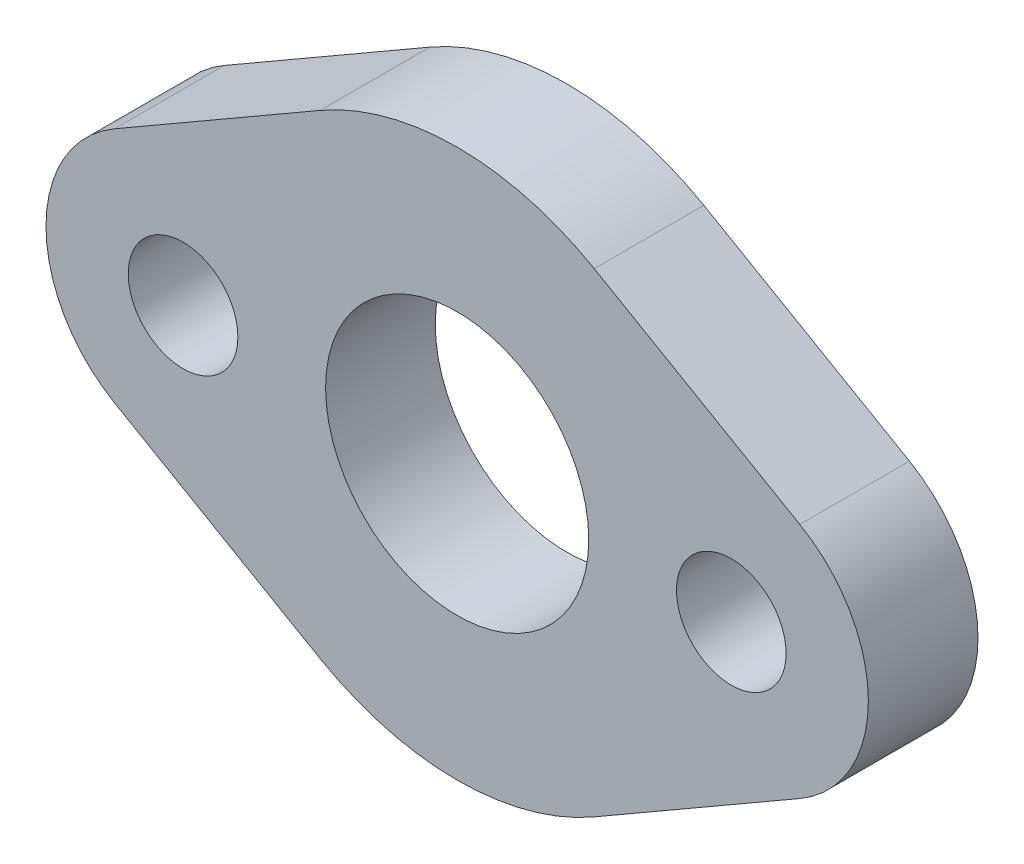
SolidWorks part; units mm, degrees
ref_plane "前视基准面" through (0, 0, 0) normal (0, 0, 1) x (1, 0, 0)
ref_plane "上视基准面" through (0, 0, 0) normal (0, 1, 0) x (1, 0, 0)
ref_plane "右视基准面" through (0, 0, 0) normal (1, 0, 0) x (0, 0, -1)
sketch "草图1" plane through (0, 0, 0) normal (0, 0, 1) x (1, 0, 0)
  line L0 (-6.25, 2.1651) -> (-2.5, 4.3301)
  line L1 (-6.25, -2.1651) -> (-2.5, -4.3301)
  line L2 (2.5, 4.3301) -> (6.25, 2.1651)
  line L3 (6.25, -2.1651) -> (2.5, -4.3301)
  line L4 (0, 0) -> (82.0854, 0) construction
  line L5 (0, 0) -> (0, 36.7987) construction
  circle A0 centre (0, 0) radius 2.4
  arc A1 (2.5, 4.3301) -> (-2.5, 4.3301) centre (0, 0) ccw
  arc A2 (6.25, -2.1651) -> (6.25, 2.1651) centre (5, 0) ccw
  arc A3 (-6.25, -2.1651) -> (-6.25, 2.1651) centre (-5, 0) cw
  arc A4 (-2.5, -4.3301) -> (2.5, -4.3301) centre (0, 0) ccw
  circle A5 centre (-5, 0) radius 1
  circle A6 centre (5, 0) radius 1
  dimension "D1" = 2.5
  dimension "D2" = 4.8
  dimension "D3" = 10
  dimension "D5" = 2
  dimension "D4" = 10
extrude "凸台-拉伸1" add sketch "草图1" along normal blind 2
